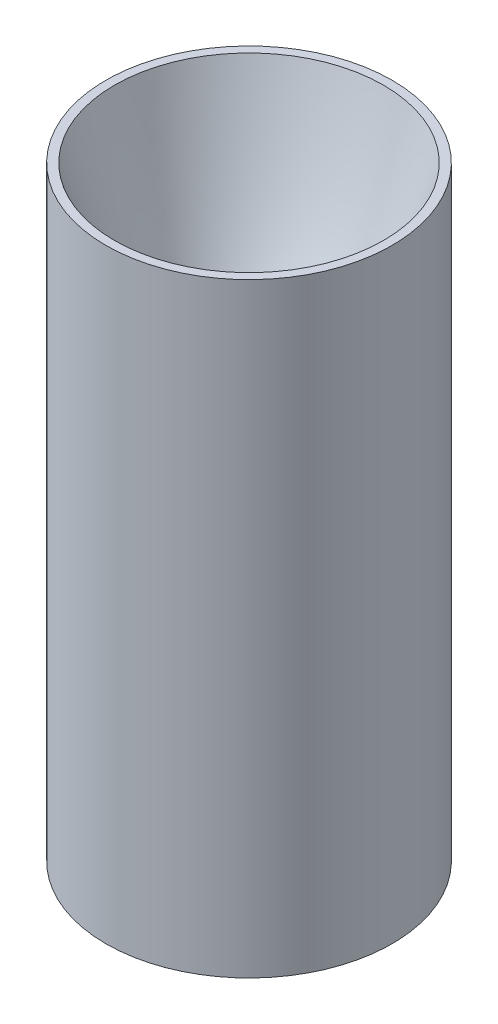
SolidWorks part; units mm, degrees
ref_plane "Front Plane" through (0, 0, 0) normal (0, 0, 1) x (1, 0, 0)
ref_plane "Top Plane" through (0, 0, 0) normal (0, 1, 0) x (1, 0, 0)
ref_plane "Right Plane" through (0, 0, 0) normal (1, 0, 0) x (0, 0, -1)
sketch "Sketch1" plane through (0, 0, 0) normal (0, 0, 1) x (1, 0, 0)
  line L0 (24.01, 0) -> (0, 0) construction
  line L1 (71.6385, 109.9273) -> (76.2, 109.9273)
  line L4 (53.7925, -59.7277) -> (53.7925, -212.1277)
  line L9 (76.2, 109.9273) -> (76.2, -212.1277)
  line L10 (76.2, -212.1277) -> (53.7925, -212.1277)
  line L11 (0, 0) -> (0, -107.6606) construction
  spline S0 degree 2 poles (26.7062, 6.5092) (49.1723, 34.636) (71.6385, 109.9273) knots 0 0 0 1 1 1 construction
  spline S1 degree 2 poles (26.7062, 6.5092) (49.1723, 34.636) (71.6385, 109.9273) knots 0 0 0 1 1 1
  spline S2 degree 4 poles (24.0378, -0.7181) (24.0369, -0.702) (24.0352, -0.674) (24.0319, -0.6548) (24.026, -0.5168) (24.0168, -0.4371) (24.0103, -0.1068) (24.0089, 0.0016) (24.013, 0.2676) (24.0194, 0.4271) (24.0315, 0.6468) (24.0524, 0.9014) (24.0861, 1.2025) (24.1374, 1.5421) (24.2015, 1.881) (24.2781, 2.2164) (24.3673, 2.5492) (24.4687, 2.8781) (24.5826, 3.2033) (24.7081, 3.5236) (24.8462, 3.8397) (24.995, 4.1493) (25.1569, 4.4548) (25.3274, 4.7513) (25.5134, 5.0457) (25.7027, 5.3255) (25.9153, 5.6107) (26.0898, 5.8329) (26.2773, 6.05) (26.4155, 6.2086) (26.6679, 6.4727) (26.7479, 6.5524) (27.0125, 6.8058) (27.099, 6.8781) (27.1963, 6.9666) (27.2147, 6.9802) (27.2373, 7.0002) knots 0 0 0 0 0 0.005192 0.010384 0.020768 0.041536 0.082569 0.102427 0.122284 0.142142 0.162 0.201716 0.241431 0.281147 0.320863 0.360578 0.400294 0.44001 0.479725 0.519441 0.559156 0.598872 0.638588 0.678303 0.718019 0.757735 0.79745 0.837166 0.857024 0.876882 0.916597 0.958047 0.979024 0.989512 1 1 1 1 1 construction
  spline S3 degree 4 poles (24.01, 0) (24.01, 0.0359) (24.0105, 0.1101) (24.013, 0.2676) (24.0194, 0.4271) (24.0315, 0.6468) (24.0524, 0.9014) (24.0861, 1.2025) (24.1374, 1.5421) (24.2015, 1.881) (24.2781, 2.2164) (24.3673, 2.5492) (24.4687, 2.8781) (24.5826, 3.2033) (24.7081, 3.5236) (24.8462, 3.8397) (24.995, 4.1493) (25.1569, 4.4548) (25.3274, 4.7513) (25.5134, 5.0457) (25.7027, 5.3255) (25.9153, 5.6107) (26.0898, 5.8329) (26.2773, 6.05) (26.4155, 6.2086) (26.5814, 6.3821) (26.6555, 6.4585) (26.7062, 6.5092) knots 0.082569 0.082569 0.082569 0.082569 0.082569 0.102427 0.122284 0.142142 0.162 0.201716 0.241431 0.281147 0.320863 0.360578 0.400294 0.44001 0.479725 0.519441 0.559156 0.598872 0.638588 0.678303 0.718019 0.757735 0.79745 0.837166 0.857024 0.876882 0.916597 0.916597 0.916597 0.916597 0.916597
  spline S4 degree 4 poles (24.1192, 2.8078) (24.1123, 2.7164) (24.0991, 2.5516) (24.0751, 2.1752) (24.0462, 1.6879) (24.0258, 1.1016) (24.0139, 0.6554) (24.0097, 0.1102) (24.0097, -0.1001) (24.0129, -0.5432) (24.0192, -0.8242) (24.0287, -1.1948) (24.0414, -1.5134) (24.0572, -1.8619) (24.0761, -2.1937) (24.1038, -2.6181) (24.1432, -3.122) (24.2142, -3.88) (24.3341, -4.8865) (24.5104, -6.0567) (24.7618, -7.3852) (25.0627, -8.7036) (25.4127, -10.0096) (25.8113, -11.3018) (26.2579, -12.5781) (26.7519, -13.8369) (27.2926, -15.0762) (27.8794, -16.2946) (28.5111, -17.4899) (29.1875, -18.6613) (29.9064, -19.8057) (30.669, -20.9239) (31.3701, -21.8744) (31.9997, -22.6734) (32.5351, -23.3204) (32.9832, -23.84) (33.4194, -24.3298) (33.8468, -24.7885) (34.1565, -25.1139) (34.523, -25.486) (34.677, -25.64) (35.0618, -26.0189) (35.3885, -26.3288) (35.8159, -26.7274) (36.1505, -27.0244) (36.4301, -27.2709) (36.5574, -27.38) (36.6257, -27.4388) (36.6605, -27.4687) knots 0 0 0 0 0 0.010393 0.020785 0.041571 0.062104 0.072371 0.082638 0.092575 0.102512 0.112449 0.122387 0.132324 0.142261 0.152198 0.162135 0.18201 0.201884 0.241633 0.281382 0.32113 0.360879 0.400628 0.440377 0.480126 0.519874 0.559623 0.599372 0.639121 0.67887 0.718618 0.758367 0.798116 0.81799 0.837865 0.857739 0.877613 0.897488 0.907425 0.917362 0.927629 0.937896 0.958429 0.979215 0.989607 0.994804 1 1 1 1 1 construction
  spline S5 degree 4 poles (24.01, 0) (24.01, -0.0705) (24.0105, -0.2136) (24.0129, -0.5432) (24.0192, -0.8242) (24.0287, -1.1948) (24.0414, -1.5134) (24.0572, -1.8619) (24.0761, -2.1937) (24.1038, -2.6181) (24.1432, -3.122) (24.2142, -3.88) (24.3341, -4.8865) (24.5104, -6.0567) (24.7618, -7.3852) (25.0627, -8.7036) (25.4127, -10.0096) (25.8113, -11.3018) (26.2579, -12.5781) (26.7519, -13.8369) (27.2926, -15.0762) (27.8794, -16.2946) (28.5111, -17.4899) (29.1875, -18.6613) (29.9064, -19.8057) (30.669, -20.9239) (31.3701, -21.8744) (31.9997, -22.6734) (32.5351, -23.3204) (32.9832, -23.84) (33.4194, -24.3298) (33.8468, -24.7885) (34.1565, -25.1139) (34.4478, -25.4096) (34.5473, -25.5099) (34.5972, -25.5598) knots 0.082638 0.082638 0.082638 0.082638 0.082638 0.092575 0.102512 0.112449 0.122387 0.132324 0.142261 0.152198 0.162135 0.18201 0.201884 0.241633 0.281382 0.32113 0.360879 0.400628 0.440377 0.480126 0.519874 0.559623 0.599372 0.639121 0.67887 0.718618 0.758367 0.798116 0.81799 0.837865 0.857739 0.877613 0.897488 0.907425 0.917362 0.917362 0.917362 0.917362 0.917362
  spline S6 degree 1 poles (34.5972, -25.5598) (43.2048, -34.1675) knots 0 0 1 1 construction
  spline S7 degree 1 poles (34.5972, -25.5598) (43.2048, -34.1675) knots 0 0 1 1
  spline S8 degree 4 poles (53.6833, -62.5354) (53.6902, -62.4466) (53.7033, -62.2738) (53.7213, -62.0018) (53.7419, -61.6601) (53.7589, -61.2922) (53.7725, -60.9659) (53.7826, -60.5754) (53.7894, -60.2941) (53.7927, -59.8333) (53.7927, -59.6305) (53.7896, -59.1817) (53.7832, -58.905) (53.7737, -58.5327) (53.7611, -58.213) (53.7414, -57.7818) (53.7113, -57.2811) (53.6671, -56.6882) (53.5882, -55.8486) (53.4884, -55.0083) (53.3676, -54.1726) (53.1977, -53.1726) (53.003, -52.1776) (52.7773, -51.1887) (52.5209, -50.2076) (52.2402, -49.2332) (51.9353, -48.2661) (51.5445, -47.1493) (51.0505, -45.8906) (50.5097, -44.6511) (49.923, -43.4329) (49.2911, -42.2373) (48.6151, -41.0663) (47.8954, -39.9211) (47.134, -38.8042) (46.4308, -37.8516) (45.8045, -37.0558) (45.2637, -36.4035) (44.8261, -35.8944) (44.4257, -35.4472) (44.0924, -35.0848) (43.7849, -34.7605) (43.585, -34.5517) (43.2762, -34.2384) (43.1268, -34.0891) (42.7386, -33.7068) (42.415, -33.3999) (41.985, -32.9988) (41.6521, -32.7035) (41.3716, -32.4561) (41.2447, -32.3474) (41.1763, -32.2885) (41.1415, -32.2585) knots 0 0 0 0 0 0.010393 0.020785 0.031178 0.041571 0.051838 0.062104 0.072371 0.082638 0.092575 0.102512 0.112449 0.122387 0.132324 0.142261 0.162135 0.18201 0.201884 0.241633 0.261507 0.281382 0.32113 0.360879 0.380754 0.400628 0.440377 0.480126 0.519874 0.559623 0.599372 0.639121 0.67887 0.718618 0.758367 0.798116 0.81799 0.837865 0.857739 0.877613 0.887551 0.897488 0.907425 0.917362 0.927629 0.937896 0.958429 0.979215 0.989607 0.994804 1 1 1 1 1 construction
  spline S9 degree 4 poles (53.7925, -59.7277) (53.7925, -59.6571) (53.7919, -59.5156) (53.7896, -59.1817) (53.7832, -58.905) (53.7737, -58.5327) (53.7611, -58.213) (53.7414, -57.7818) (53.7113, -57.2811) (53.6671, -56.6882) (53.5882, -55.8486) (53.4884, -55.0083) (53.3676, -54.1726) (53.1977, -53.1726) (53.003, -52.1776) (52.7773, -51.1887) (52.5209, -50.2076) (52.2402, -49.2332) (51.9353, -48.2661) (51.5445, -47.1493) (51.0505, -45.8906) (50.5097, -44.6511) (49.923, -43.4329) (49.2911, -42.2373) (48.6151, -41.0663) (47.8954, -39.9211) (47.134, -38.8042) (46.4308, -37.8516) (45.8045, -37.0558) (45.2637, -36.4035) (44.8261, -35.8944) (44.4257, -35.4472) (44.0924, -35.0848) (43.7849, -34.7605) (43.585, -34.5517) (43.3553, -34.3187) (43.2547, -34.2173) (43.2048, -34.1675) knots 0.082638 0.082638 0.082638 0.082638 0.082638 0.092575 0.102512 0.112449 0.122387 0.132324 0.142261 0.162135 0.18201 0.201884 0.241633 0.261507 0.281382 0.32113 0.360879 0.380754 0.400628 0.440377 0.480126 0.519874 0.559623 0.599372 0.639121 0.67887 0.718618 0.758367 0.798116 0.81799 0.837865 0.857739 0.877613 0.887551 0.897488 0.907425 0.917362 0.917362 0.917362 0.917362 0.917362
  spline S10 degree 2 poles (36.8348, 6.4922) (58.5836, 47.0333) (81.7275, 109.9275) knots 0.442127 0.442127 0.442127 0.998319 0.998319 0.998319 construction
  dimension "D1" = 152.4
  dimension "D2" = 24.01
  dimension "D3" = 152.4
revolve "Revolve2" add sketch "Sketch1" angle 360 about L11
hole_wizard "3/8-24 Tapped Hole1" positions "Sketch3" profile "Sketch4" tap size "3/8-24" standard "ANSI Inch"
sketch "Sketch3" plane through (0, -212.1277, 0) normal (0, -1, 0) x (-1, 0, 0)
  circle A1 centre (0, 0) radius 66.675 construction
  point P10 (-66.675, 0)
  point P20 (0, 0)
  dimension "D1" = 133.35
sketch "Sketch4" plane through (66.675, -212.1277, 0) normal (1, 0, 0) x (0, 0, -1)
  line L0 (0, 0) -> (0, 27.5347)
  line L1 (0, 27.5347) -> (4.2164, 25.0012)
  line L2 (4.2164, 25.0012) -> (4.2164, 0)
  line L5 (4.2164, 0) -> (0, 0)
  line L10 (0, 27.5347) -> (-4.2164, 25.0012) construction
  line L11 (0, -6.35) -> (0, 107.95) construction
  dimension "Tap Drill Dia." = 8.4328
  dimension "Tap Drill Depth" = 25.0012
  dimension "Drill Angle" = 118
cosmetic thread "Hole Thread1" parameters "D1"=20, "D2"=9.525
pattern_circular "CirPattern1" count 8 over 360 about axis through (0, 0, 0) along (0, 1, 0) of "3/8-24 Tapped Hole1"
cosmetic thread "Hole Thread2" parameters "D1"=20, "D2"=9.525
cosmetic thread "Hole Thread3" parameters "D1"=20, "D2"=9.525
cosmetic thread "Hole Thread4" parameters "D1"=20, "D2"=9.525
cosmetic thread "Hole Thread5" parameters "D1"=20, "D2"=9.525
cosmetic thread "Hole Thread6" parameters "D1"=20, "D2"=9.525
cosmetic thread "Hole Thread7" parameters "D1"=20, "D2"=9.525
cosmetic thread "Hole Thread8" parameters "D1"=20, "D2"=9.525
sketch "Sketch8" [suppressed] plane through (0, -212.1275, 0) normal (0, -1, 0) x (1, 0, 0)
  circle A0 centre (0, 0) radius 53.8815 construction
  circle A1 centre (0, 0) radius 76.49 construction
  circle A2 centre (0, 0) radius 65.2002 construction
  dimension "D1" = 107.7631
  dimension "D2" = 130.4004
  dimension "D3" = 152.98
sketch "Sketch9" plane through (0, -212.1277, 0) normal (0, -1, 0) x (1, 0, 0)
  circle A0 centre (0, 0) radius 53.8815
  circle A1 centre (0, 0) radius 56.8815
  dimension "D1" = 3
extrude "Cut-Extrude1" [suppressed] cut sketch "Sketch9" against normal blind 6
hole_wizard "1/4 (0.2500) Dowel Hole1" positions "Sketch11" profile "Sketch12" hole size "1/4" standard "ANSI Inch"
sketch "Sketch11" plane through (0, -212.1277, 0) normal (0, -1, 0) x (-1, 0, 0)
  line L6 (0, 0) -> (61.5997, -25.5154) construction
  line L8 (0, 0) -> (-61.5997, 25.5154) construction
  line L9 (0, 0) -> (-66.675, 0) construction
  circle A0 centre (0, 0) radius 66.675 construction
  point P22 (61.5997, -25.5154)
  point P28 (-61.5997, 25.5154)
  dimension "D1" = 22.5
sketch "Sketch12" plane through (61.5997, -212.1277, -25.5154) normal (1, 0, 0) x (0, 0, -1)
  line L0 (0, 0) -> (0, 11.8137)
  line L1 (0, 11.8137) -> (3.175, 9.906)
  line L2 (3.175, 9.906) -> (3.175, 0)
  line L5 (3.175, 0) -> (0, 0)
  line L10 (0, 11.8137) -> (-3.175, 9.906) construction
  line L11 (0, -6.35) -> (0, 107.95) construction
  dimension "Hole Dia." = 6.35
  dimension "Hole Depth" = 9.906
  dimension "Drill Angle" = 118
sketch "Sketch14" plane through (0, -212.1277, 0) normal (0, -1, 0) x (1, 0, 0)
  circle A0 centre (0, 0) radius 53.7925 construction
  circle A1 centre (0, 0) radius 53.7925 construction
  circle A2 centre (0, 0) radius 55.38
  circle A3 centre (0, 0) radius 57.412
  dimension "D1" = 1.5875
  dimension "D2" = 2.032
extrude "gasket_groove" [suppressed] cut sketch "Sketch14" against normal blind 1.27
